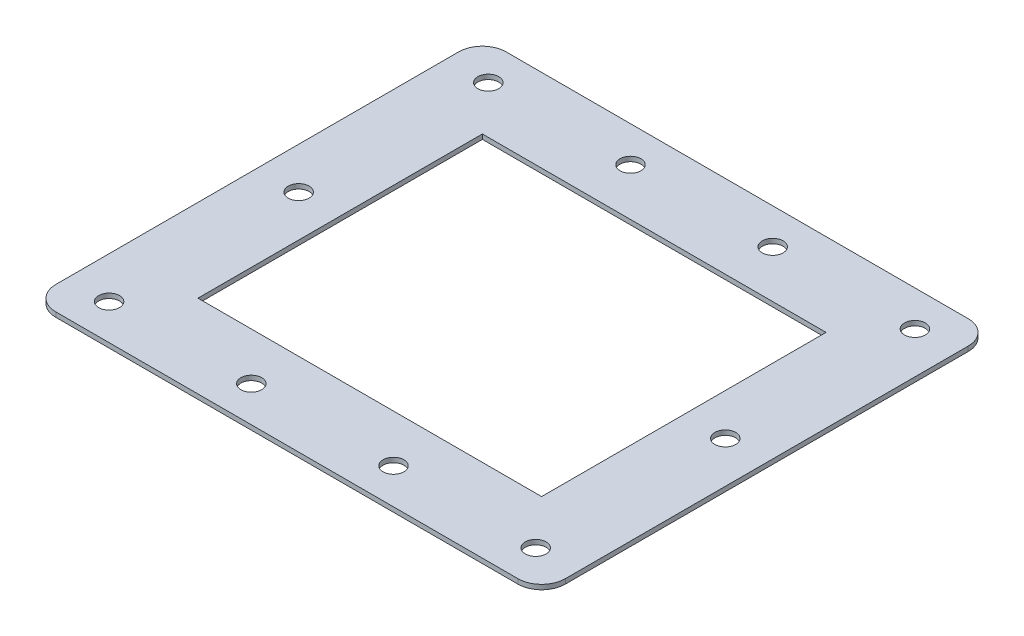
SolidWorks part; units mm, degrees
material "AISI 304"
ref_plane "Спереди" through (0, 0, 0) normal (0, 0, 1) x (1, 0, 0)
ref_plane "Сверху" through (0, 0, 0) normal (0, 1, 0) x (1, 0, 0)
ref_plane "Справа" through (0, 0, 0) normal (1, 0, 0) x (0, 0, -1)
sketch "Эскиз1" plane through (0, 0, 0) normal (0, 1, 0) x (1, 0, 0)
  line L0 (0, 60) -> (0, -60) construction
  line L1 (-72.5, 60) -> (72.5, 60)
  line L2 (-72.5, 60) -> (-72.5, -60)
  line L3 (-72.5, -60) -> (72.5, -60)
  line L4 (72.5, 60) -> (72.5, -60)
  line L5 (-72.5, 0) -> (72.5, 0) construction
  line L6 (-107.5, 95) -> (-107.5, -95)
  line L7 (-107.5, -95) -> (107.5, -95)
  line L8 (107.5, 95) -> (107.5, -95)
  line L9 (-107.5, 95) -> (107.5, 95)
  circle A0 centre (-90, 80) radius 4.4
  circle A11 centre (-90, -80) radius 4.4
  circle A19 centre (-90, 0) radius 4.4
  circle A20 centre (-30, -80) radius 4.4
  circle A22 centre (-30, 80) radius 4.4
  circle A23 centre (30, -80) radius 4.4
  circle A25 centre (30, 80) radius 4.4
  circle A26 centre (90, -80) radius 4.4
  circle A27 centre (90, 0) radius 4.4
  circle A28 centre (90, 80) radius 4.4
  circle A29 centre (-30, 0) radius 4.4 [skipped]
  circle A30 centre (30, 0) radius 4.4 [skipped]
  point P8 (0, 0)
  dimension "D4" = 8.8
  dimension "D1" = 145
  dimension "D2" = 120
  dimension "D5" = 90
  dimension "D6" = 80
  dimension "D3" = 35
  dimension "D7" = 2
  dimension "D8" = 4
extrude "Бобышка-Вытянуть1" add sketch "Эскиз1" along normal blind 2
fillet "Скругление1" radius 10 4 edges at (-107.5, 1, -95) (107.5, 1, -95) (-107.5, 1, 95) (107.5, 1, 95)
